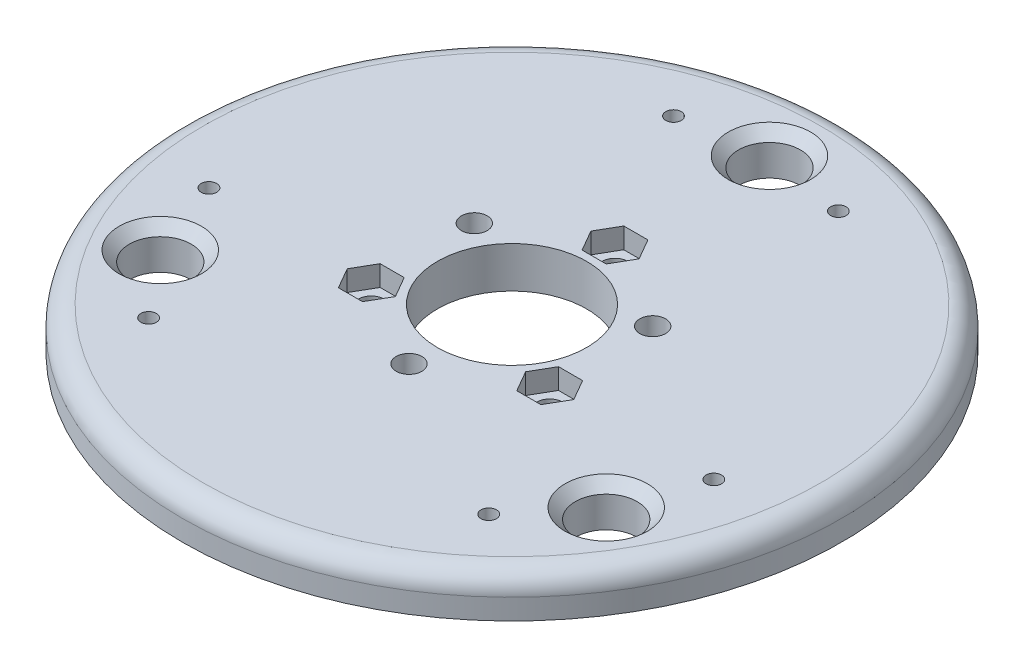
SolidWorks part; units mm, degrees
ref_plane "Спереди" through (0, 0, 0) normal (0, 0, 1) x (1, 0, 0)
ref_plane "Сверху" through (0, 0, 0) normal (0, 1, 0) x (1, 0, 0)
ref_plane "Справа" through (0, 0, 0) normal (1, 0, 0) x (0, 0, -1)
sketch "Эскиз1" plane through (0, 0, 0) normal (0, 1, 0) x (1, 0, 0)
  circle A3 centre (0, 0) radius 32
  circle A4 centre (0, 0) radius 7.25
  circle A6 centre (0, 0) radius 25 construction
  circle A7 centre (0, 25) radius 3
  circle A8 centre (21.6506, -12.5) radius 3
  circle A9 centre (-21.6506, -12.5) radius 3
  dimension "D4" = 64
  dimension "D1" = 14.5
  dimension "D2" = 50
  dimension "D3" = 6
  dimension "D5" = 3
extrude "Бобышка-Вытянуть1" add sketch "Эскиз1" along normal blind 4
fillet "Скругление1" radius 2 1 edges at (0, 4, 32)
sketch "Эскиз2" plane through (0, 4, 0) normal (0, 1, 0) x (1, 0, 0)
  circle A0 centre (0, 0) radius 10 construction
  circle A1 centre (0, 10) radius 1.25
  circle A2 centre (8.6603, 5) radius 1.25
  circle A3 centre (8.6603, -5) radius 1.25
  circle A4 centre (0, -10) radius 1.25
  circle A5 centre (-8.6603, -5) radius 1.25
  circle A6 centre (-8.6603, 5) radius 1.25
  dimension "D3" = 6
  dimension "D1" = 20
  dimension "D2" = 2.5
extrude "Вырез-Вытянуть1" cut sketch "Эскиз2" against normal through all
sketch "Эскиз3" plane through (0, 4, 0) normal (0, 1, 0) x (1, 0, 0)
  line L0 (9.8294, -7.025) -> (10.9985, -5)
  line L1 (1.1691, 7.975) -> (2.3383, 10)
  line L2 (2.3383, 10) -> (1.1691, 12.025)
  line L3 (1.1691, 12.025) -> (-1.1691, 12.025)
  line L4 (-1.1691, 12.025) -> (-2.3383, 10)
  line L5 (-2.3383, 10) -> (-1.1691, 7.975)
  line L6 (-1.1691, 7.975) -> (1.1691, 7.975)
  line L7 (10.9985, -5) -> (9.8294, -2.975)
  line L8 (9.8294, -2.975) -> (7.4911, -2.975)
  line L9 (7.4911, -2.975) -> (6.322, -5)
  line L10 (6.322, -5) -> (7.4911, -7.025)
  line L11 (7.4911, -7.025) -> (9.8294, -7.025)
  line L12 (-10.9985, -5) -> (-9.8294, -7.025)
  line L13 (-9.8294, -7.025) -> (-7.4911, -7.025)
  line L14 (-7.4911, -7.025) -> (-6.322, -5)
  line L15 (-6.322, -5) -> (-7.4911, -2.975)
  line L16 (-7.4911, -2.975) -> (-9.8294, -2.975)
  line L17 (-9.8294, -2.975) -> (-10.9985, -5)
  circle A0 centre (0, 10) radius 2.025 construction
  circle A1 centre (8.6603, -5) radius 2.025 construction
  circle A2 centre (-8.6603, -5) radius 2.025 construction
  circle A3 centre (-8.6603, -5) radius 1.25 construction
  point P1 (0, 7.975)
  dimension "D1" = 4.05
  dimension "D2" = 3
extrude "Вырез-Вытянуть2" cut sketch "Эскиз3" against normal blind 2
sketch "Эскиз4" plane through (0, 0, 0) normal (0, -1, 0) x (1, 0, 0)
  line L0 (7.4911, -7.025) -> (9.8294, -7.025)
  line L1 (-1.1691, 7.975) -> (1.1691, 7.975)
  line L2 (1.1691, 7.975) -> (2.3383, 10)
  line L3 (2.3383, 10) -> (1.1691, 12.025)
  line L4 (1.1691, 12.025) -> (-1.1691, 12.025)
  line L5 (-1.1691, 12.025) -> (-2.3383, 10)
  line L6 (-2.3383, 10) -> (-1.1691, 7.975)
  line L7 (9.8294, -7.025) -> (10.9985, -5)
  line L8 (10.9985, -5) -> (9.8294, -2.975)
  line L9 (9.8294, -2.975) -> (7.4911, -2.975)
  line L10 (7.4911, -2.975) -> (6.322, -5)
  line L11 (6.322, -5) -> (7.4911, -7.025)
  line L12 (-9.8294, -2.975) -> (-10.9985, -5)
  line L13 (-10.9985, -5) -> (-9.8294, -7.025)
  line L14 (-9.8294, -7.025) -> (-7.4911, -7.025)
  line L15 (-7.4911, -7.025) -> (-6.322, -5)
  line L16 (-6.322, -5) -> (-7.4911, -2.975)
  line L17 (-7.4911, -2.975) -> (-9.8294, -2.975)
  circle A0 centre (0, 10) radius 2.025 construction
  circle A1 centre (8.6603, -5) radius 2.025 construction
  circle A2 centre (-8.6603, -5) radius 2.025 construction
  circle A3 centre (8.6603, -5) radius 1.25 construction
  dimension "D1" = 4.05
  dimension "D2" = 3
extrude "Вырез-Вытянуть3" cut sketch "Эскиз4" against normal blind 2
chamfer "Фаска1" distance 1 angle 45 3 edges at (0, 4, -22) (-21.6506, 4, 15.5) (21.6506, 4, 15.5)
sketch "Эскиз5" plane through (0, 4, 0) normal (0, 1, 0) x (1, 0, 0)
  line L0 (0, 0) -> (0, 25) construction
  line L1 (-8, 23.6854) -> (8, 23.6854) construction
  circle A0 centre (0, 0) radius 25 construction
  circle A1 centre (8, 23.6854) radius 0.75
  circle A2 centre (-8, 23.6854) radius 0.75
  circle A3 centre (24.5122, -4.9145) radius 0.75
  circle A4 centre (16.5122, -18.7709) radius 0.75
  circle A5 centre (-16.5122, -18.7709) radius 0.75
  circle A6 centre (-24.5122, -4.9145) radius 0.75
  dimension "D2" = 1.5
  dimension "D3" = 1.5
  dimension "D1" = 16
  dimension "D4" = 3
extrude "Вырез-Вытянуть4" cut sketch "Эскиз5" against normal through all
equation "\"motor_diameter\"= 30"
equation "\"mm_diameter\"= IIF ( \"motor_diameter\" < 34 , 41 , \"motor_diameter\" + 8 )"
equation "\"upper_shafts_diameter\"= 5"
equation "\"upper_shats_length\"= 180"
equation "\"upper_bearing_d1\"= 10"
equation "\"upper_bearing_d2\"= 5"
equation "\"upper_bearing_h\"= 15"
equation "\"lower_shafts_diameter\"= 5"
equation "\"lower_shafts_length\"= 180"
equation "\"lower_bearing_d1\"= 10"
equation "\"lower_bearing_d2\"= 5"
equation "\"lower_bearing_h\"= 15"
equation "\"print_offset\"= 0.5"
equation "\"bh_screws_d\"= 2"
equation "\"bh_screws_h\"= 20"
equation "\"bh_screws_hh_d\"= 3.4"
equation "\"bh_screws_hh_h\"= 2"
equation "\"bh_nut_d\"= 3.8"
equation "\"bh_nut_h\"= 2"
equation "\"motor_screws_d\"= 3"
equation "\"motor_screws_h\"= 16"
equation "\"motor_screws_hh_d\"= 5.5"
equation "\"motor_screws_hh_h\"= 3"
equation "\"plate_hole_distance\"= 25.4"
equation "\"plate_screws_d\"= 6.5"
equation "\"shafts_diameter\"= IIF ( \"mm_diameter\" < 42 , 42 + 8 , \"mm_diameter\" + 8 )"
equation "\"D4@Эскиз1\"= \"system_radius\" * 2"
equation "\"central_hole_diameter\"= 8"
equation "\"bh_thikness\"= 4"
equation "\"D2@Эскиз1\"=\"shafts_diameter\""
equation "\"D3@Эскиз1\"= \"lower_shafts_diameter\" + 1"
equation "\"D1@Бобышка-Вытянуть1\"=\"bh_thikness\""
equation "\"D2@Эскиз2\"=\"bh_screws_d\"+\"print_offset\""
equation "\"D1@Эскиз3\"=\"bh_nut_d\"+\"print_offset\"/2"
equation "\"D1@Вырез-Вытянуть2\"=\"bh_nut_h\""
equation "\"D1@Эскиз4\"=\"bh_nut_d\"+\"print_offset\"/2"
equation "\"D1@Вырез-Вытянуть3\"=\"bh_nut_h\""
equation "\"D2@Эскиз5\"=\"bh_screws_d\"-\"print_offset\""
equation "\"D3@Эскиз5\"=\"D2@Эскиз5\""
equation "\"ends_screws_d\"= 4"
equation "\"ends_screws_h\"= 16"
equation "\"ends_screws_hh_d\"= 6.7"
equation "\"ends_screws_hh_h\"= 4.1"
equation "\"ends_nut_d\"= 6.8"
equation "\"ends_nut_h\"= 3"
equation "\"system_radius\" = ( \"shafts_diameter\" + 12 + \"bh_thikness\" / 2 ) / 2"
equation "\"encoder_distance\"= \"system_radius\" + 4"
equation "\"tape_position\"= \"encoder_distance\" - 2 + 3.9 + 1.7 / 2"
equation "\"D1@Эскиз1\"=\"print_offset\"+14.00мм"
equation "\"ft_sensor_d1\" = 9.8"
equation "\"ft_sensor_d2\"= 24.9"
equation "\"ft_sensor_h\"= 7"
equation "\"carbon_pipe_d\"= 14"
